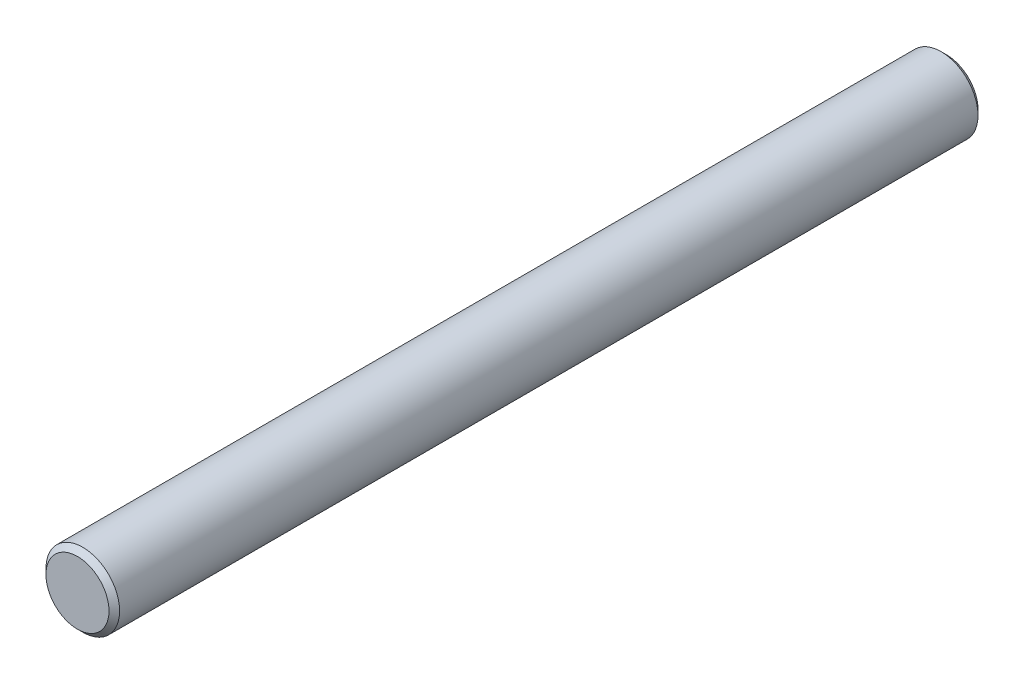
SolidWorks part; units mm, degrees
ref_plane "Front Plane" through (0, 0, 0) normal (0, 0, 1) x (1, 0, 0)
ref_plane "Top Plane" through (0, 0, 0) normal (0, 1, 0) x (1, 0, 0)
ref_plane "Right Plane" through (0, 0, 0) normal (1, 0, 0) x (0, 0, -1)
sketch "Sketch2" plane through (0, 0, 0) normal (0, 0, 1) x (1, 0, 0)
  circle A0 centre (0, 0) radius 3.475
  dimension "D1" = 6.95
extrude "Boss-Extrude1" add sketch "Sketch2" along normal mid plane 82
chamfer "Chamfer1" distance 0.5 angle 45 2 edges at (3.475, 0, -41) (3.475, 0, 41)
